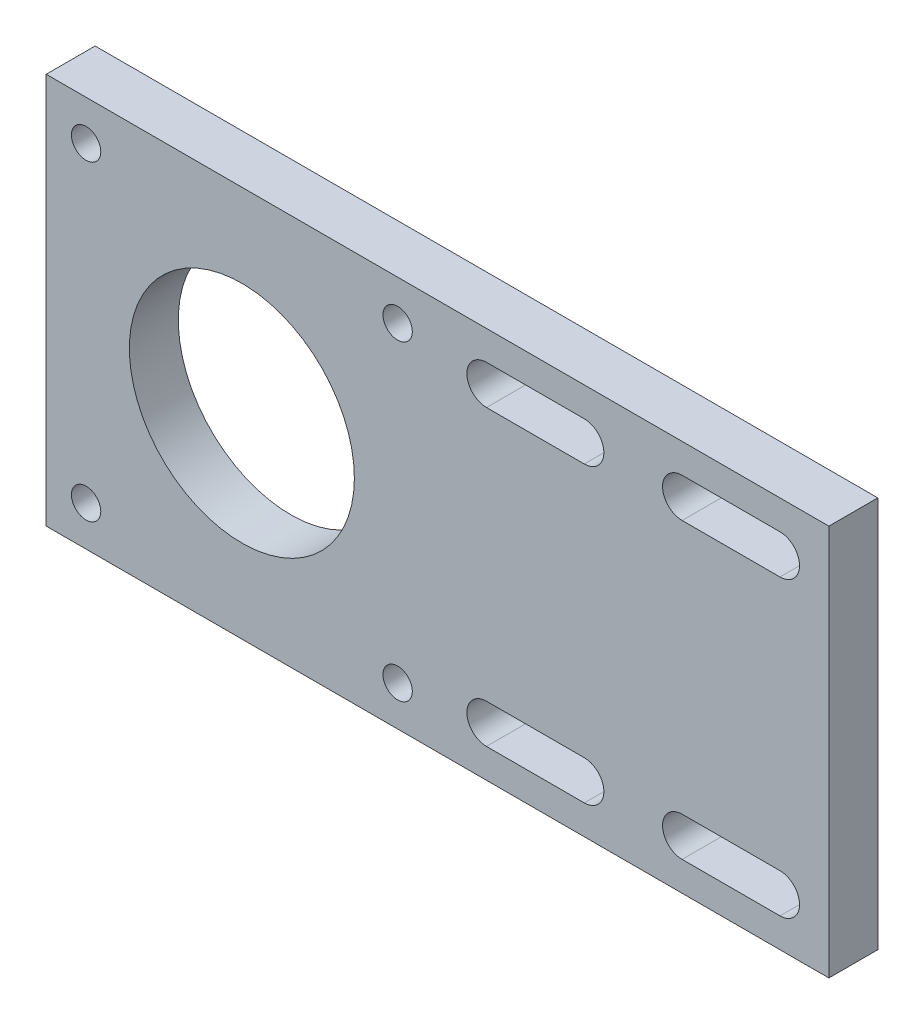
SolidWorks part; units mm, degrees
ref_plane "Front Plane" through (0, 0, 0) normal (0, 0, 1) x (1, 0, 0)
ref_plane "Top Plane" through (0, 0, 0) normal (0, 1, 0) x (1, 0, 0)
ref_plane "Right Plane" through (0, 0, 0) normal (1, 0, 0) x (0, 0, -1)
sketch "Sketch1" plane through (0, 0, 0) normal (0, 0, 1) x (1, 0, 0)
  line L0 (0, 0) -> (19.6767, 0) construction
  line L1 (0, 0) -> (0, 18.5995) construction
  line L2 (-15.922, 15.922) -> (15.922, 15.922) construction
  line L3 (-20, 20) -> (-20, -20)
  line L4 (-20, -20) -> (60, -20)
  line L5 (60, -20) -> (60, 20)
  line L6 (60, 20) -> (-20, 20)
  line L7 (44.4398, 15) -> (22.1541, 15) construction
  line L8 (44.4398, -15) -> (22.1541, -15) construction
  line L9 (25, 15) -> (35, 15) construction
  line L10 (25, 17) -> (35, 17)
  line L11 (25, 13) -> (35, 13)
  line L12 (30, 20) -> (30, -20) construction
  line L13 (50, -20) -> (50, 20) construction
  line L14 (45, 15) -> (55, 15) construction
  line L15 (45, 17) -> (55, 17)
  line L16 (45, 13) -> (55, 13)
  line L17 (45, -15) -> (55, -15) construction
  line L18 (45, -13) -> (55, -13)
  line L19 (45, -17) -> (55, -17)
  line L20 (25, -15) -> (35, -15) construction
  line L21 (25, -13) -> (35, -13)
  line L22 (25, -17) -> (35, -17)
  arc A0 (25, 17) -> (25, 13) centre (25, 15) ccw
  arc A1 (35, 13) -> (35, 17) centre (35, 15) ccw
  arc A2 (45, 17) -> (45, 13) centre (45, 15) ccw
  arc A3 (55, 13) -> (55, 17) centre (55, 15) ccw
  arc A4 (45, -13) -> (45, -17) centre (45, -15) ccw
  arc A5 (55, -17) -> (55, -13) centre (55, -15) ccw
  arc A6 (25, -13) -> (25, -17) centre (25, -15) ccw
  arc A7 (35, -17) -> (35, -13) centre (35, -15) ccw
  point P16 (30, 15)
  point P26 (0, 0)
  point P27 (29.4112, 11.2979)
  point P29 (50, 15)
  point P36 (50, -15)
  point P43 (30, -15)
  point P48 (15.5255, 6.6122)
  point P49 (25.0523, 12)
  point P50 (35, 10)
  point P51 (46.7918, 8)
  point P52 (0, 0)
  point P53 (-14.5799, 19.2758)
  point P54 (40, 10.3661)
  point P55 (36.1113, 16.2874)
  point P56 (0, 0)
  point P57 (69.3837, 20)
  circle B0 centre (-15.922, 15.922) radius 1.5
  circle B1 centre (15.922, 15.922) radius 1.5
  circle B2 centre (15.922, -15.922) radius 1.5
  circle B3 centre (-15.922, -15.922) radius 1.5
  circle B4 centre (0, 0) radius 11.5
  dimension "D3" = 4
  dimension "D4" = 40
  dimension "D5" = 20
  dimension "D6" = 10
  dimension "D7" = 30
  dimension "D9" = 15
  dimension "D2" = 10
  dimension "D1" = 20
sketch_block_instance "Fixation Nema 17-1"
sketch_block "Fixation Nema 17"
extrude "Boss-Extrude1" add sketch "Sketch1" along normal blind 5
